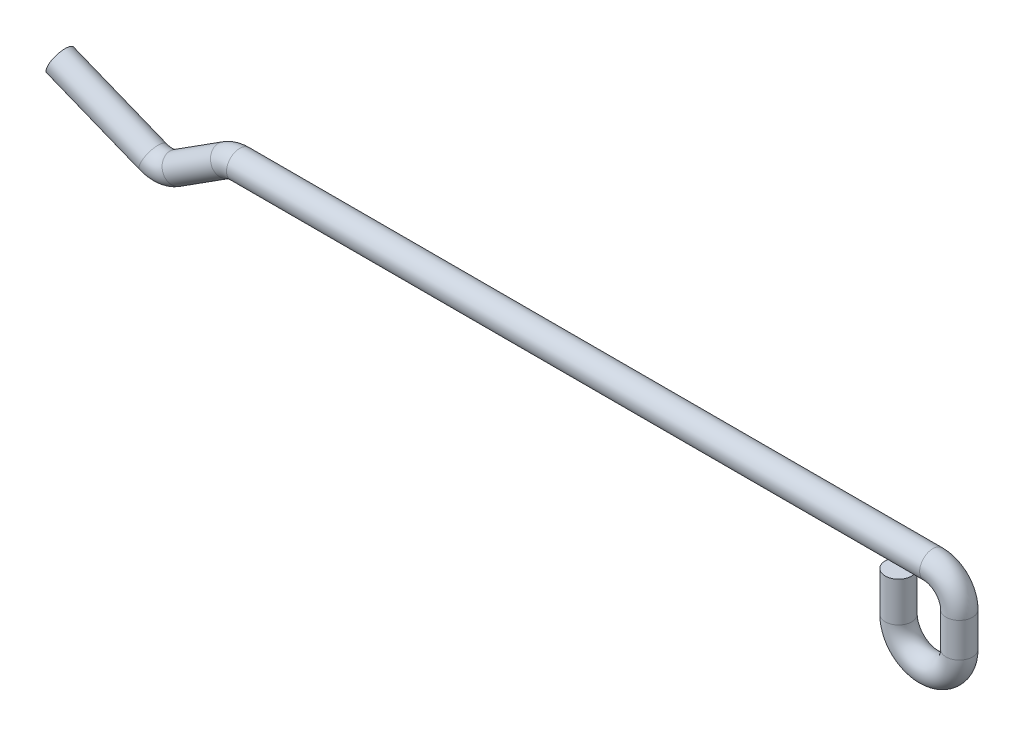
SolidWorks part; units mm, degrees
ref_plane "Face" through (0, 0, 0) normal (0, 0, 1) x (1, 0, 0)
ref_plane "Dessus" through (0, 0, 0) normal (0, 1, 0) x (1, 0, 0)
ref_plane "Droite" through (0, 0, 0) normal (1, 0, 0) x (0, 0, -1)
sketch "Esquisse1" plane through (0, 0, 0) normal (0, 0, 1) x (1, 0, 0)
  line L0 (4.6, -3) -> (4.6, -0.4)
  line L1 (2.6, 1.6) -> (-49.8165, 1.6)
  line L2 (-50.8919, 1.2863) -> (-54.5514, -1.0476)
  line L3 (-56.371, -1.2178) -> (-63.4, 1.6)
  line L4 (0, -3) -> (0, 0)
  arc A0 (0, -3) -> (4.6, -3) centre (2.3, -3) ccw
  arc A1 (4.6, -0.4) -> (2.6, 1.6) centre (2.6, -0.4) ccw
  arc A2 (-49.8165, 1.6) -> (-50.8919, 1.2863) centre (-49.8165, -0.4) ccw
  arc A3 (-54.5514, -1.0476) -> (-56.371, -1.2178) centre (-55.6268, 0.6386) cw
  point P11 (4.6, 1.6)
  point P14 (-50.4, 1.6)
  point P17 (-55.4175, -1.6)
  point P18 (2.3, -5.3)
  dimension "D1" = 2.3
  dimension "D8" = 2
  dimension "D2" = 4.6
  dimension "D3" = 55
  dimension "D4" = 68
  dimension "D5" = 8.6
  dimension "D6" = 3.2
  dimension "D7" = 3
sketch "Esquisse2" plane through (0, 0, 0) normal (0, 1, 0) x (1, 0, 0)
  circle A0 centre (0, 0) radius 1
  dimension "D1" = 2
sweep "Balayage1" add profiles "Esquisse2" path "Esquisse1"
move or copy body "Body-Move/Copy1" [suppressed] bodies to move or copy 101 parameters "D1"=0, "D2"=0, "D3"=0
